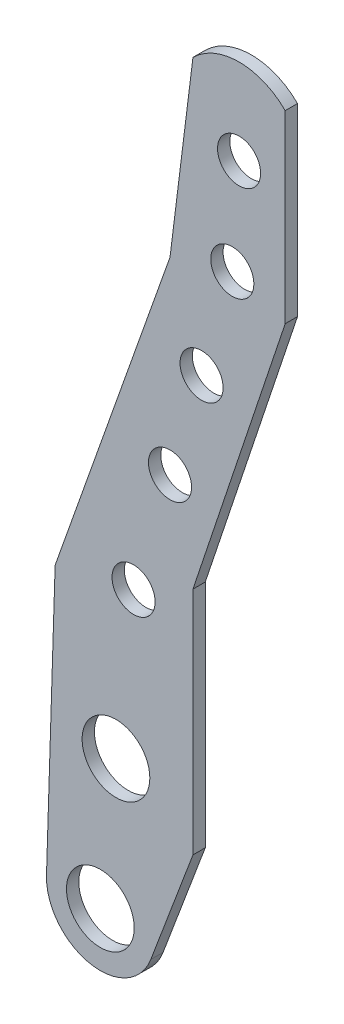
SolidWorks part; units mm, degrees
ref_plane "Front Plane" through (0, 0, 0) normal (0, 0, 1) x (1, 0, 0)
ref_plane "Top Plane" through (0, 0, 0) normal (0, 1, 0) x (1, 0, 0)
ref_plane "Right Plane" through (0, 0, 0) normal (1, 0, 0) x (0, 0, -1)
sketch "Sketch1" plane through (0, 0, 0) normal (0, 0, 1) x (1, 0, 0)
  line B0 (43.6562, 145.4782) -> (60.0385, 194.4865)
  line B1 (60.0385, 194.4865) -> (60.0385, 254.4271)
  line B2 (30.0781, 254.4271) -> (22.6293, 194.4865)
  line B3 (22.6293, 194.4865) -> (-14.6833, 89.2308)
  line B4 (-14.6833, 89.2308) -> (-14.6833, -0.057)
  line B5 (14.7807, -0.057) -> (30.0781, 30.1029)
  line B6 (30.0781, 30.1029) -> (30.0781, 104.8586)
  line B7 (30.0781, 104.8586) -> (43.6562, 145.4782)
  arc B8 (60.0385, 254.4271) -> (30.0781, 254.4271) centre (45.0583, 239.4469) ccw
  arc B9 (-14.6833, -0.057) -> (14.7807, -0.057) centre (0.0487, -0.057) ccw
  circle B10 centre (-5.2372, 41.2368) radius 3
  circle B11 centre (1.7318, 52.1805) radius 3
  circle B12 centre (21.4304, 50.1742) radius 3
  circle B13 centre (9.5747, 59.1115) radius 3
  circle B14 centre (1.7318, 67.8664) radius 3
  circle B15 centre (-5.2372, 59.1115) radius 3
  circle B16 centre (-4.9682, 76.648) radius 3
  circle B17 centre (10.1372, 104.8586) radius 3.7338
  circle B18 centre (1.7318, 107.7204) radius 4
  circle B19 centre (-4.5729, 25.5702) radius 4
  circle B20 centre (5.6027, 24.4116) radius 4
  circle B21 centre (19.4271, 25.5702) radius 4
  circle B22 centre (0.0487, -0.057) radius 5
  circle B23 centre (10.1372, 81.8976) radius 7.366
  circle B24 centre (22.6293, 133.2845) radius 7.366
  circle B25 centre (32.8774, 166.3648) radius 7.366
  circle B26 centre (42.8552, 200.5742) radius 7.366
  circle B27 centre (45.0583, 232.7881) radius 7.366
sketch_block_instance "break pedal-1"
sketch_block "break pedal"
sketch "Sketch2" plane through (0, 0, 0) normal (0, 0, 1) x (1, 0, 0)
  line L0 (30.0781, 30.1029) -> (30.0781, 104.8586) construction
  line L1 (30.0781, 104.8586) -> (43.6562, 145.4782) construction
  line L2 (43.6562, 145.4782) -> (60.0385, 194.4865) construction
  line L3 (60.0385, 194.4865) -> (60.0385, 254.4271) construction
  line L4 (30.0781, 254.4271) -> (22.6293, 194.4865) construction
  line L5 (22.6293, 194.4865) -> (-14.6833, 89.2308) construction
  line L6 (30.0781, 30.1029) -> (30.0781, 104.8586)
  line L7 (30.0781, 104.8586) -> (43.6562, 145.4782)
  line L8 (43.6562, 145.4782) -> (60.0385, 194.4865)
  line L9 (60.0385, 194.4865) -> (60.0385, 254.4271)
  line L10 (30.0781, 254.4271) -> (22.6293, 194.4865)
  line L11 (22.6293, 194.4865) -> (-14.6833, 89.2308)
  line L12 (30.0781, 30.1029) -> (16.3709, -6.184)
  line L13 (-14.6833, 89.2308) -> (-17.4912, 0.5538)
  line L14 (22.6293, 133.2845) -> (32.8774, 166.3648) construction
  line L15 (32.8774, 166.3648) -> (42.8552, 200.5742) construction
  line L16 (42.8552, 200.5742) -> (45.0583, 232.7881) construction
  line L17 (22.6293, 133.2845) -> (10.7925, 95.0759) construction
  line L18 (0, 0) -> (10.7925, 95.0759) construction
  circle A0 centre (0, 0) radius 11
  arc A1 (-17.4912, 0.5538) -> (16.3709, -6.184) centre (0, 0) ccw
  arc A2 (60.0385, 254.4271) -> (30.0781, 254.4271) centre (45.0583, 239.4469) ccw construction
  arc A3 (60.0385, 254.4271) -> (30.0781, 254.4271) centre (45.0583, 239.4469) ccw
  circle A4 centre (45.0583, 232.7881) radius 7
  circle A5 centre (42.8552, 200.5742) radius 7
  circle A6 centre (32.8774, 166.3648) radius 7
  circle A7 centre (22.6293, 133.2845) radius 7
  circle A9 centre (10.7925, 95.0759) radius 7
  circle A10 centre (5.0755, 44.7128) radius 11
  dimension "D1" = 35
  dimension "D2" = 22
  dimension "D3" = 14
  dimension "D4" = 40
  dimension "D5" = 45
  dimension "D6" = 22
extrude "Boss-Extrude1" add sketch "Sketch2" along normal blind 4
